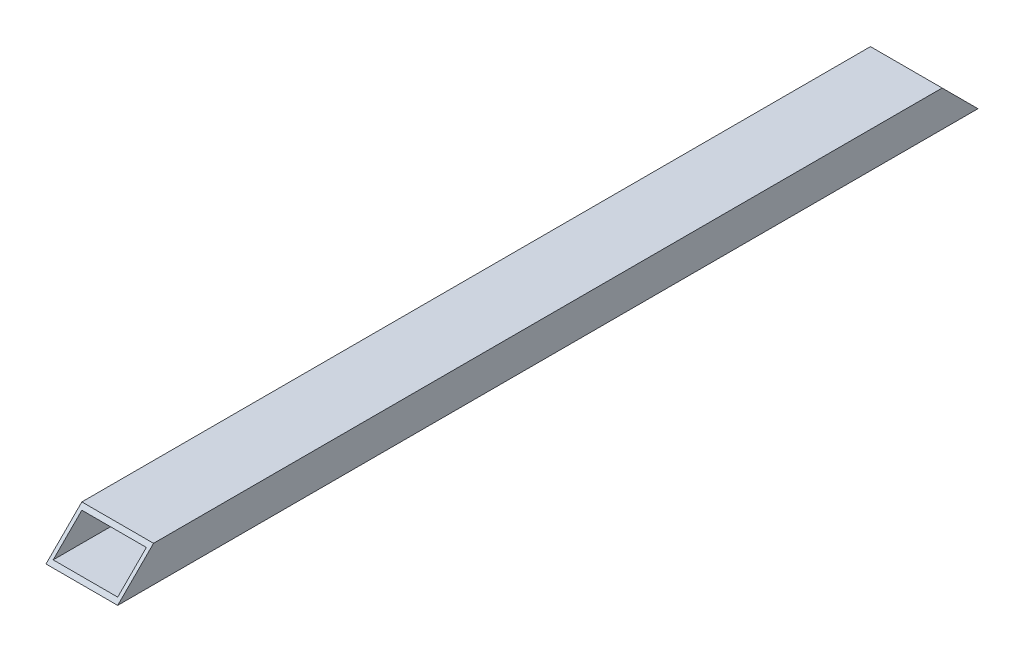
SolidWorks part; units mm, degrees
material "AISI 1010 Steel, hot rolled bar"
ref_plane "Front Plane" through (0, 0, 0) normal (0, 0, 1) x (1, 0, 0)
ref_plane "Top Plane" through (0, 0, 0) normal (0, 1, 0) x (1, 0, 0)
ref_plane "Right Plane" through (0, 0, 0) normal (1, 0, 0) x (0, 0, -1)
sketch "Sketch1" plane through (0, 0, 0) normal (0, 0, 1) x (1, 0, 0)
  line L0 (2, -2) -> (38, -2)
  line L1 (0, 0) -> (40, 0)
  line L2 (0, 0) -> (0, -20)
  line L3 (0, -20) -> (40, -20)
  line L4 (40, 0) -> (40, -20)
  line L5 (38, -2) -> (38, -18)
  line L6 (2, -18) -> (38, -18)
  line L7 (2, -2) -> (2, -18)
  dimension "D1" = 40
  dimension "D2" = 20
  dimension "D3" = 2
extrude "Boss-Extrude1" add sketch "Sketch1" along normal blind 480
sketch "Sketch2" plane through (40, 0, 0) normal (1, 0, 0) x (0, 0, -1)
  line L0 (-480, -20) -> (-460, 0)
  line L1 (-480, 0) -> (0, 0) construction
  line L2 (-480, -20) -> (0, -20) construction
  line L3 (-460, 0) -> (-480, 0)
  line L4 (-480, 0) -> (-480, -20)
  line L5 (-240, 0) -> (-240, -20) construction
  line L6 (-20, 0) -> (0, 0)
  line L7 (0, -20) -> (-20, 0)
  line L8 (0, 0) -> (0, -20)
  dimension "D1" = 45
extrude "Cut-Extrude1" cut sketch "Sketch2" against normal through all
